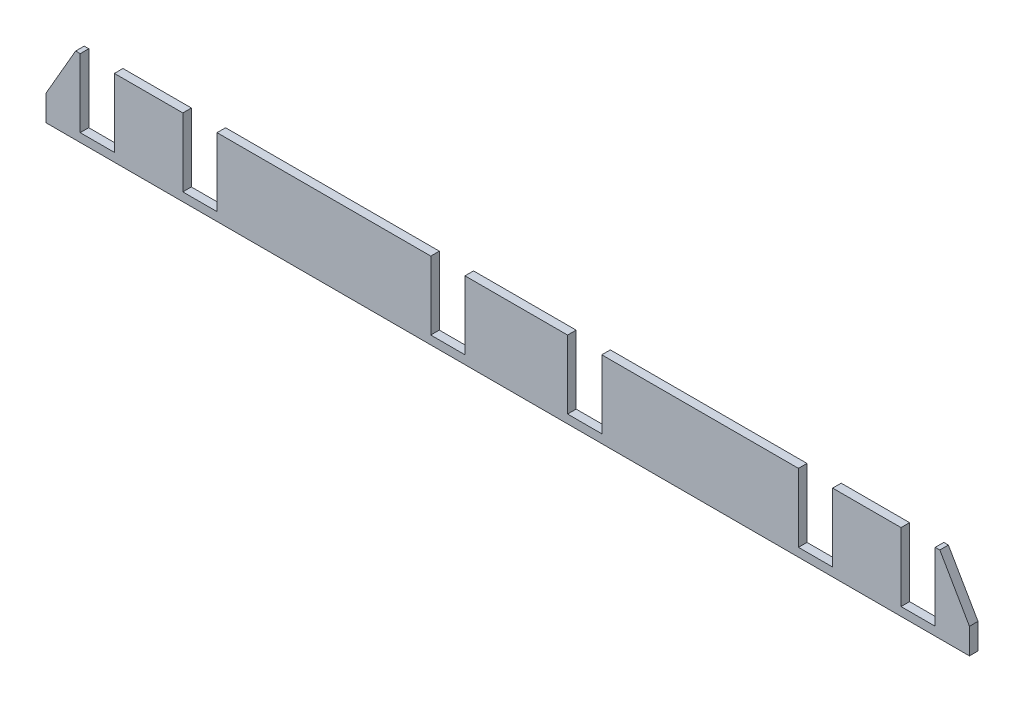
SolidWorks part; units mm, degrees
ref_plane "Plan de face" through (0, 0, 0) normal (0, 0, 1) x (1, 0, 0)
ref_plane "Plan de dessus" through (0, 0, 0) normal (0, 1, 0) x (1, 0, 0)
ref_plane "Plan de droite" through (0, 0, 0) normal (1, 0, 0) x (0, 0, -1)
sketch "Esquisse1" plane through (0, 0, 0) normal (0, 0, 1) x (1, 0, 0)
  line L0 (0, 50) -> (1080, 50) construction
  line L1 (0, 0) -> (1080, 0)
  line L2 (0, 0) -> (0, 90)
  line L4 (1080, 0) -> (1080, 90)
  line L5 (40, 90) -> (80, 90) construction
  line L6 (40, 90) -> (40, 10)
  line L7 (40, 10) -> (80, 10)
  line L8 (80, 90) -> (80, 10)
  line L9 (200, 90) -> (200, 10)
  line L10 (160, 90) -> (200, 90) construction
  line L11 (160, 90) -> (160, 10)
  line L12 (160, 10) -> (200, 10)
  line L13 (540, 0) -> (540, 120) construction
  line L14 (450, 90) -> (200, 90)
  line L15 (450, 90) -> (490, 90) construction
  line L16 (450, 90) -> (450, 10)
  line L17 (450, 10) -> (490, 10)
  line L18 (490, 90) -> (490, 10)
  line L19 (450, 10) -> (200, 10) construction
  line L20 (1040, 10) -> (1000, 10)
  line L21 (1040, 90) -> (1040, 10)
  line L22 (1040, 90) -> (1000, 90) construction
  line L23 (1000, 90) -> (1000, 10)
  line L24 (920, 90) -> (920, 10)
  line L25 (920, 90) -> (880, 90) construction
  line L26 (880, 90) -> (880, 10)
  line L27 (920, 10) -> (880, 10)
  line L28 (880, 90) -> (650, 90)
  line L29 (610, 90) -> (650, 90) construction
  line L30 (610, 90) -> (610, 10)
  line L31 (610, 10) -> (650, 10)
  line L32 (650, 90) -> (650, 10)
  line L33 (880, 10) -> (650, 10) construction
  line L34 (0, 90) -> (40, 90)
  line L35 (80, 90) -> (160, 90)
  line L36 (490, 90) -> (610, 90)
  line L37 (920, 90) -> (1000, 90)
  line L38 (1040, 90) -> (1080, 90)
  point P11 (80, 50)
  point P18 (200, 50)
  dimension "D1" = 1080
  dimension "D2" = 40
  dimension "D3" = 80
  dimension "D4" = 40
  dimension "D6" = 10
  dimension "D8" = 80
  dimension "D9" = 40
  dimension "D10" = 290
  dimension "D11" = 40
  dimension "D12" = 270
  dimension "D7" = 2
extrude "Boss.-Extru.1" add sketch "Esquisse1" along normal blind 10
chamfer "Chanfrein1" distance 60 angle 30 2 edges at (0, 90, 5) (1080, 90, 5)
